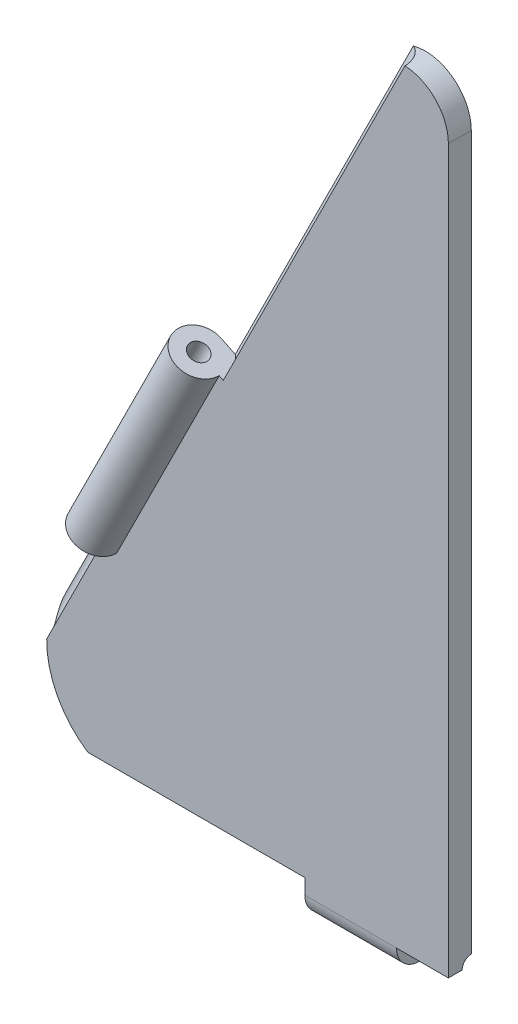
SolidWorks part; units mm, degrees
ref_plane "前视基准面" through (0, 0, 0) normal (0, 0, 1) x (1, 0, 0)
ref_plane "上视基准面" through (0, 0, 0) normal (0, 1, 0) x (1, 0, 0)
ref_plane "右视基准面" through (0, 0, 0) normal (1, 0, 0) x (0, 0, -1)
sketch "草图1" plane through (0, 0, 5) normal (0, 0, 1) x (1, 0, 0)
  line L0 (-531.2593, 335.4243) -> (-597.8429, 202.2571)
  line L1 (-579.9544, 173.3129) -> (-512.3151, 173.3129)
  line L2 (-512.3151, 173.3129) -> (-512.3151, 330.9522)
  arc A0 (-579.9544, 173.3129) -> (-597.8429, 202.2571) centre (-579.9544, 193.3129) cw
  arc A1 (-512.3151, 330.9522) -> (-531.2593, 335.4243) centre (-522.3151, 330.9522) ccw
  point P2 (-598.8986, 200.1457)
  point P4 (-582.3151, 173.3129)
  point P6 (-612.3151, 173.3129)
  point P10 (-512.3151, 373.3129)
  dimension "D2" = 20
  dimension "D3" = 10
  dimension "D1" = 200
extrude "凸台-拉伸1" add sketch "草图1" along normal blind 5
sketch "草图2" plane through (0, 173.3129, 0) normal (0, -1, 0) x (1, 0, 0)
  line L0 (-612.3151, 7.5) -> (-512.3151, 7.5) construction
  line L5 (-612.3151, 10) -> (-612.3151, 5) construction
  line L6 (-512.3151, 10) -> (-512.3151, 5) construction
  line L7 (-546.1347, 5) -> (-546.1347, 10) construction
  line L8 (-579.9544, 5) -> (-512.3151, 5) construction
  line L9 (-579.9544, 10) -> (-512.3151, 10) construction
  line L15 (-543.6347, 5) -> (-523.6347, 5)
  line L16 (-543.6347, 5) -> (-543.6347, 10)
  line L17 (-543.6347, 10) -> (-523.6347, 10)
  line L18 (-523.6347, 5) -> (-523.6347, 10)
  dimension "D1" = 2.5
  dimension "D2" = 20
sketch "草图5" plane through (-559.1772, 279.5886, 0) normal (-0.8944, 0.4472, 0) x (0, 0, 1)
  line L0 (5, 62.4262) -> (5, -86.4592) construction
  line L1 (5, -17.0165) -> (10, -17.0165)
  line L2 (5, -17.0165) -> (5, -67.0165)
  line L3 (5, -67.0165) -> (10, -67.0165)
  line L4 (10, -17.0165) -> (10, -67.0165)
  line L5 (10, 62.4262) -> (10, -86.4592) construction
  line L6 (7.5, 104.7869) -> (7.5, -118.8199) construction
  line L7 (10, 104.7869) -> (5, 104.7869) construction
  line L8 (10, -118.8199) -> (5, -118.8199) construction
  line L9 (5, -12.0165) -> (10, -12.0165) construction
  dimension "D1" = 5
  dimension "D2" = 50
revolve "旋转1" add sketch "草图5" angle 360 about L4
revolve "旋转2" add sketch "草图2" angle 360 about L15
sketch "草图7" plane through (-543.6347, 0, 0) normal (-1, 0, 0) x (0, 0, 1)
  circle A1 centre (5, 173.3129) radius 2
  dimension "D1" = 4
sketch "草图8" plane through (-29.9707, -59.9414, 0) normal (-0.4472, -0.8944, 0) x (0.8944, -0.4472, 0)
  circle A0 centre (-625.1791, 10) radius 2
extrude "切除-拉伸2" cut sketch "草图8" against normal through all both and the other way through all contours A0
sketch "草图12" plane through (-543.6347, 0, 0) normal (-1, 0, 0) x (0, 0, 1)
  circle A0 centre (5, 173.3129) radius 2
  circle A1 centre (5, 173.3129) radius 6
  arc A2 (5, 178.3129) -> (10, 173.3129) centre (5, 173.3129) ccw construction
extrude "切除-拉伸6" cut sketch "草图12" along normal through all
sketch "草图13" plane through (-543.6347, 0, 0) normal (-1, 0, 0) x (0, 0, 1)
  circle A0 centre (5, 173.3129) radius 2
  dimension "D1" = 4
extrude "切除-拉伸7" cut sketch "草图13" against normal through all both and the other way through all
sketch "草图11" plane through (-7.61, -15.22, 0) normal (0.4472, 0.8944, 0) x (0.8944, -0.4472, 0)
  circle A0 centre (-625.1791, -10) radius 6
extrude "切除-拉伸5" cut sketch "草图11" along normal through all
scale "缩放比例1" scale about origin uniform scaling yes scale factor 0.5
